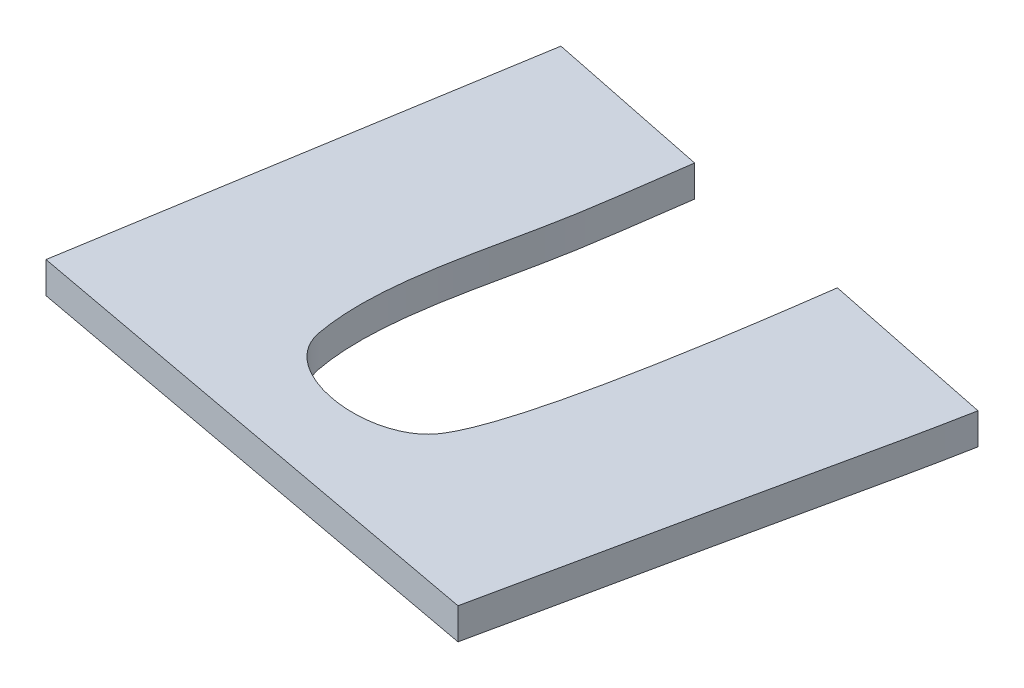
SolidWorks part; units mm, degrees
ref_plane "Front Plane" through (0, 0, 0) normal (0, 0, 1) x (1, 0, 0)
ref_plane "Top Plane" through (0, 0, 0) normal (0, 1, 0) x (1, 0, 0)
ref_plane "Right Plane" through (0, 0, 0) normal (1, 0, 0) x (0, 0, -1)
sketch "Sketch1" plane through (0, 0, 0) normal (0, 1, 0) x (1, 0, 0)
  line L0 (65.6854, -45.7865) -> (145.9282, -45.7865) construction
  line L2 (105.4165, 31.1383) -> (105.1558, -6.4062)
  line L3 (105.1558, -6.4062) -> (104.7647, -24.3962)
  line L4 (104.7647, -24.3962) -> (88.339, -24.1355)
  line L5 (88.339, -24.1355) -> (87.5568, 23.7076)
  line L6 (87.5568, 23.7076) -> (86.6443, 23.4469)
  line L7 (86.6443, 23.4469) -> (81.169, -31.0447)
  line L8 (81.169, -31.0447) -> (64.8737, -29.4804)
  line L9 (64.8737, -29.4804) -> (68.9149, 25.272)
  line L10 (68.9149, 25.272) -> (67.872, 25.1416)
  line L11 (67.872, 25.1416) -> (61.3539, -10.3171)
  line L12 (56.5305, -35.6074) -> (40.3655, -32.6091)
  line L13 (40.3655, -32.6091) -> (50.4034, 28.531)
  line L14 (50.4034, 28.531) -> (49.3605, 28.4007)
  line L15 (49.3605, 28.4007) -> (39.844, -6.1454)
  line L16 (32.8045, -31.0447) -> (17.0306, -26.7428)
  line L17 (17.0306, -26.7428) -> (21.0718, -9.7956)
  line L18 (21.0718, -9.7956) -> (27.7203, 14.5822)
  line L19 (27.7203, 14.5822) -> (34.3688, 40.6548)
  line L20 (39.844, 36.3528) -> (44.5371, 35.1795)
  line L21 (44.5371, 35.1795) -> (43.2335, 30.4865)
  line L22 (43.2335, 30.4865) -> (38.6708, 31.7901)
  line L23 (38.6708, 31.7901) -> (39.844, 36.3528)
  line L24 (57.7037, 32.3116) -> (62.5272, 31.399)
  line L25 (62.5272, 31.399) -> (61.6146, 26.706)
  line L26 (61.6146, 26.706) -> (56.9216, 27.4881)
  line L27 (56.9216, 27.4881) -> (57.7037, 32.3116)
  line L28 (75.8242, 29.7043) -> (80.6476, 29.1828)
  line L29 (80.6476, 29.1828) -> (80.2565, 24.4898)
  line L30 (80.2565, 24.4898) -> (75.4331, 24.8809)
  line L31 (75.4331, 24.8809) -> (75.8242, 29.7043)
  line L32 (37.3672, 28.9221) -> (42.9727, 27.3578)
  line L33 (31.7616, 7.4123) -> (37.3672, 28.9221)
  line L34 (94.2053, 28.6614) -> (99.0287, 28.531)
  line L35 (99.0287, 28.531) -> (98.8984, 23.838)
  line L36 (98.8984, 23.838) -> (94.2053, 23.9683)
  line L37 (94.2053, 23.9683) -> (94.2053, 28.6614)
  line L38 (55.8787, 24.4898) -> (61.4843, 23.5773)
  line L39 (61.4843, 23.5773) -> (61.6146, 23.0558)
  line L40 (74.6509, 21.7522) -> (80.5172, 21.2307)
  line L41 (93.6838, 20.7093) -> (99.5502, 20.5789)
  line L42 (99.4198, -9.0134) -> (93.6838, -8.8831)
  line L43 (31.6312, -14.8797) -> (26.156, -13.3154)
  line L44 (77.2581, -15.2708) -> (71.5222, -14.7494)
  line L45 (54.0536, -19.5728) -> (48.3176, -18.5299)
  line L46 (93.6838, -10.1867) -> (99.5502, -10.3171)
  line L47 (25.7649, -14.4887) -> (31.3705, -15.9226)
  line L48 (23.4183, -24.0051) -> (25.7649, -14.4887)
  line L49 (71.3918, -15.9226) -> (77.1278, -16.4441)
  line L50 (48.0569, -19.5728) -> (53.7929, -20.7461)
  spline S0 degree 3 poles (34.3688, 40.6548) (40.7566, 39.047) (47.0864, 37.1883) (53.5321, 35.8313) (59.4811, 34.5789) (65.4868, 33.5633) (71.5222, 32.833) (82.7525, 31.4742) (94.1059, 31.3316) (105.4165, 31.1383) knots 0 0 0 0 1 1 1 2 2 2 3 3 3 3
  spline S1 degree 3 poles (61.3539, -10.3171) (60.5564, -15.1018) (59.9234, -19.9204) (58.877, -24.657) (58.0717, -28.3021) (57.3126, -31.9573) (56.5305, -35.6074) knots 0 0 0 0 1 1 1 2 2 2 2
  spline S2 degree 3 poles (39.844, -6.1454) (38.6037, -10.974) (37.5703, -15.8635) (36.0635, -20.6157) (34.9627, -24.0875) (33.8908, -27.5684) (32.8045, -31.0447) knots 0 0 0 0 1 1 1 2 2 2 2
  spline S3 degree 3 poles (42.9727, 27.3578) (42.6098, 25.543) (42.0183, 23.7712) (41.5388, 22.0129) (40.5659, 18.4459) (39.615, 14.8641) (38.6708, 11.3232) (38.3128, 9.9807) (37.6374, 5.782) (36.3242, 5.0657) (36.0465, 4.9143) (35.7159, 4.8919) (35.4117, 4.805) knots 0 0 0 0 1 1 1 2 2 2 3 3 3 4 4 4 4
  spline S4 degree 3 poles (35.4117, 4.805) (35.3683, 4.8485) (35.3416, 4.9233) (35.2813, 4.9354) (34.8955, 5.0126) (34.4939, 4.9886) (34.1081, 5.0657) (32.6203, 5.3633) (32.0189, 5.8682) (31.7616, 7.4123) knots 0 0 0 0 1 1 1 2 2 2 3 3 3 3
  spline S5 degree 3 poles (61.6146, 23.0558) (61.5712, 23.0123) (61.4951, 22.9859) (61.4843, 22.9254) (61.1889, 21.28) (60.9974, 19.6171) (60.7021, 17.9717) (60.4799, 16.7336) (60.0077, 14.6452) (59.7895, 13.409) (59.5288, 11.9315) (59.2681, 10.4541) (59.0074, 8.9766) (58.5651, 6.4706) (58.3671, 3.9272) (57.5734, 1.546) (57.2884, 0.6909) (56.5034, 0.8671) (56.009, 0.3727) knots 0 0 0 0 1 1 1 2 2 2 3 3 3 4 4 4 5 5 5 6 6 6 6
  spline S6 degree 3 poles (56.009, 0.3727) (55.9656, 0.4161) (55.9396, 0.4949) (55.8787, 0.5031) (55.5536, 0.5464) (53.0297, 0.6407) (52.6196, 1.2852) (51.9043, 2.4092) (52.2987, 3.9943) (52.4892, 5.0657) (53.3606, 9.9671) (54.1038, 14.7799) (54.9661, 19.6664) (55.2268, 21.1438) (55.4876, 22.6213) (55.7483, 24.0987) (55.759, 24.1592) (55.8592, 24.1708) (55.8787, 24.2291) (55.9061, 24.3115) (55.8787, 24.4029) (55.8787, 24.4898) knots 0 0 0 0 1 1 1 2 2 2 3 3 3 4 4 4 5 5 5 6 6 6 7 7 7 7
  spline S7 degree 3 poles (80.5172, 21.2307) (80.0392, 15.6686) (79.6003, 10.1029) (79.0832, 4.5443) (79.0775, 4.4831) (78.963, 4.4746) (78.9529, 4.4139) (78.826, 3.6525) (78.8807, 1.9872) (77.91, 1.546) (77.5837, 1.3977) (77.2251, 1.3001) (76.8671, 1.2852) (74.9681, 1.2061) (73.2767, 1.3602) (73.2169, 3.6318) (73.1849, 4.8488) (73.2635, 6.0673) (73.3473, 7.2819) (73.3515, 7.3432) (73.4721, 7.3511) (73.4776, 7.4123) (73.9079, 12.1889) (74.2598, 16.9722) (74.6509, 21.7522) knots 0 0 0 0 1 1 1 2 2 2 3 3 3 4 4 4 5 5 5 6 6 6 7 7 7 8 8 8 8
  spline S8 degree 3 poles (99.5502, 20.5789) (99.5292, 18.1925) (100.7408, 9.6804) (99.1591, 4.9354) (99.0178, 4.5115) (98.3729, 4.0848) (97.9858, 4.0228) (97.3343, 3.9186) (94.7895, 3.5063) (94.2053, 4.6747) (94.0209, 5.0434) (93.8276, 5.4359) (93.8142, 5.8479) (93.6532, 10.7993) (93.7273, 15.7555) (93.6838, 20.7093) knots 0 0 0 0 1 1 1 2 2 2 3 3 3 4 4 4 5 5 5 5
  spline S9 degree 3 poles (93.6838, -8.8831) (93.7381, -4.9776) (93.2303, -1.8325) (94.0749, 1.546) (94.2734, 2.34) (95.3786, 2.8868) (96.1607, 2.8496) (96.8606, 2.8163) (97.5625, 2.7409) (98.2465, 2.5889) (98.4265, 2.5489) (98.5481, 2.3589) (98.6376, 2.1978) (98.8264, 1.858) (99.0648, 1.5319) (99.1591, 1.1549) (99.329, 0.4751) (99.4018, -0.2305) (99.4198, -0.9309) (99.4889, -3.6242) (99.4198, -6.3193) (99.4198, -9.0134) knots 0 0 0 0 1 1 1 2 2 2 3 3 3 4 4 4 5 5 5 6 6 6 7 7 7 7
  spline S10 degree 3 poles (26.156, -13.3154) (26.5473, -11.1629) (27.1698, -8.9703) (27.8507, -6.9276) (28.181, -5.9365) (28.5376, -4.1432) (29.2847, -3.1471) (30.1612, -1.9784) (33.0544, -2.5643) (33.717, -3.6686) (33.8584, -3.9042) (33.9663, -4.1761) (33.9777, -4.4507) (34.0665, -6.5814) (33.3414, -8.5642) (32.8045, -10.5778) (32.4111, -12.053) (32.0449, -13.4318) (31.6312, -14.8797) knots 0 0 0 0 1 1 1 2 2 2 3 3 3 4 4 4 5 5 5 6 6 6 6
  spline S11 degree 3 poles (71.5222, -14.7494) (71.7395, -12.0987) (71.9178, -9.4445) (72.174, -6.7973) (72.1799, -6.7361) (72.2915, -6.727) (72.3044, -6.6669) (72.4857, -5.8207) (72.4934, -4.085) (73.4776, -3.5382) (74.7635, -2.8238) (77.5508, -3.0117) (77.7796, -4.8418) (78.1927, -8.1469) (77.532, -12.0533) (77.2581, -15.2708) knots 0 0 0 0 1 1 1 2 2 2 3 3 3 4 4 4 5 5 5 5
  spline S12 degree 3 poles (48.3176, -18.5299) (48.4682, -17.6074) (49.3932, -9.6418) (50.7945, -7.8402) (51.7213, -6.6485) (54.6235, -7.2853) (55.2268, -8.492) (55.8006, -9.6395) (55.3934, -11.4371) (55.2268, -12.4029) (55.0096, -13.663) (54.8079, -14.926) (54.575, -16.1834) (54.3669, -17.3074) (54.2274, -18.443) (54.0536, -19.5728) knots 0 0 0 0 1 1 1 2 2 2 3 3 3 4 4 4 5 5 5 5
  spline S13 degree 3 poles (99.5502, -10.3171) (99.5067, -13.3154) (99.5054, -16.3146) (99.4198, -19.3121) (99.418, -19.3735) (99.3015, -19.3822) (99.2894, -19.4424) (99.1051, -20.3644) (99.0318, -21.7625) (97.7251, -21.9193) (97.6585, -21.9273) (95.19, -22.2702) (94.5964, -21.5282) (94.042, -20.8353) (93.862, -19.7496) (93.8142, -18.921) (93.7141, -17.1852) (93.7098, -15.445) (93.6838, -13.7065) (93.6663, -12.5333) (93.6838, -11.36) (93.6838, -10.1867) knots 0 0 0 0 1 1 1 2 2 2 3 3 3 4 4 4 5 5 5 6 6 6 7 7 7 7
  spline S14 degree 3 poles (31.3705, -15.9226) (30.9772, -17.7579) (30.4209, -19.4915) (29.9365, -21.2675) (29.4951, -22.8858) (29.203, -24.6491) (28.2418, -26.0909) (28.0279, -26.4117) (27.2093, -26.8922) (26.8078, -26.8731) (26.4958, -26.8583) (24.4443, -26.5211) (23.9398, -25.9606) (23.5046, -25.477) (23.4904, -24.5814) (23.4183, -24.0051) knots 0 0 0 0 1 1 1 2 2 2 3 3 3 4 4 4 5 5 5 5
  spline S15 degree 3 poles (77.1278, -16.4441) (77.1137, -16.6412) (76.8294, -26.002) (75.5634, -27.3946) (75.0354, -27.9754) (74.4265, -27.9481) (73.7383, -28.0464) knots 0 0 0 0 1 1 1 2 2 2 2
  spline S16 degree 3 poles (73.7383, -28.0464) (73.1325, -27.4405) (72.0165, -28.1085) (71.3918, -27.3946) (70.9276, -26.864) (70.7525, -25.5861) (70.74, -25.048) (70.7087, -23.7006) (70.7863, -22.352) (70.8704, -21.0068) (70.8742, -20.9455) (70.9945, -20.9376) (71.0007, -20.8764) (71.1697, -19.2287) (71.2615, -17.5739) (71.3918, -15.9226) knots 0 0 0 0 1 1 1 2 2 2 3 3 3 4 4 4 5 5 5 5
  spline S17 degree 3 poles (53.7929, -20.7461) (53.7097, -21.2553) (52.6819, -29.4762) (51.4463, -31.1751) (50.4846, -32.4974) (47.0812, -32.066) (46.7533, -30.2625) (46.3263, -27.9143) (47.1317, -25.3533) (47.5354, -23.0926) (47.7439, -21.925) (47.8831, -20.7461) (48.0569, -19.5728) knots 0 0 0 0 1 1 1 2 2 2 3 3 3 4 4 4 4
  dimension "D1" = 16.35
extrude "Boss-Extrude1" add sketch "Sketch1" along normal blind 1
sketch "Sketch2" plane through (0, 1, 0) normal (0, 1, 0) x (1, 0, 0)
  line L0 (34.3688, 40.6548) -> (34.1217, 39.6858)
  line L1 (34.3688, 40.6548) -> (27.7203, 14.5822) construction
  line L6 (105.1558, -6.4062) -> (105.4165, 31.1383) construction
  line L7 (105.4095, 30.1383) -> (105.4165, 31.1383)
  arc A0 (34.3688, 40.6548) -> (105.4165, 31.1383) centre (102.0623, 276.0676) ccw
  arc A1 (34.1217, 39.6858) -> (105.4095, 30.1383) centre (102.1959, 277.0586) ccw
  dimension "D1" = 1
  dimension "D2" = 1
  dimension "D3" = 1
extrude "Boss-Extrude2" add sketch "Sketch2" along normal blind 2.42 and the other way blind 1
fillet "Fillet1" radius 0.5 2 edges at (69.5427, 3.42, -33.2836) (69.4162, 3.42, -32.3027)
sketch "Sketch3" plane through (0, 1, 0) normal (0, 1, 0) x (1, 0, 0)
  line L20 (37.3672, 28.9221) -> (42.9727, 27.3578)
  line L39 (42.9727, 27.3578) -> (48.6429, 25.7958)
  line L40 (39.844, -6.1454) -> (49.3605, 28.4007) construction
  line L41 (37.3672, 28.9221) -> (31.7427, 30.3564)
  line L42 (34.1217, 39.6858) -> (27.7203, 14.5822) construction
  line L43 (31.7427, 30.3564) -> (31.9898, 31.3253)
  line L45 (48.9085, 26.7599) -> (48.6429, 25.7958)
  line L46 (31.9898, 31.3253) -> (48.9085, 26.7599)
  line L47 (55.8787, 24.4898) -> (61.4843, 23.5773)
  line L48 (61.4843, 23.5773) -> (67.4072, 22.613)
  line L49 (61.3539, -10.3171) -> (67.872, 25.1416) construction
  line L50 (55.8787, 24.4898) -> (49.9011, 25.4712)
  line L51 (50.4034, 28.531) -> (40.3655, -32.6091) construction
  line L52 (49.9011, 25.4712) -> (50.0631, 26.458)
  line L53 (67.4072, 22.613) -> (67.588, 23.5966)
  line L54 (50.0631, 26.458) -> (67.588, 23.5966)
  line L55 (74.6509, 21.7522) -> (80.5172, 21.2307)
  line L56 (80.5172, 21.2307) -> (74.6509, 21.7522) construction
  line L57 (80.5172, 21.2307) -> (86.3626, 20.6434)
  line L58 (81.169, -31.0447) -> (86.6443, 23.4469) construction
  line L59 (74.6509, 21.7522) -> (68.6876, 22.1923)
  line L60 (68.9149, 25.272) -> (64.8737, -29.4804) construction
  line L61 (68.6876, 22.1923) -> (68.7612, 23.1896)
  line L62 (86.3626, 20.6434) -> (86.4625, 21.6384)
  line L63 (68.7612, 23.1896) -> (86.4625, 21.6384)
  line L64 (93.6838, 20.7093) -> (99.5502, 20.5789)
  line L65 (99.5502, 20.5789) -> (105.3432, 20.5789)
  line L66 (105.1558, -6.4062) -> (105.4095, 30.1383) construction
  line L67 (93.6838, 20.7093) -> (87.6036, 20.8444)
  line L68 (87.5568, 23.7076) -> (88.339, -24.1355) construction
  line L69 (87.6036, 20.8444) -> (87.5873, 21.8443)
  line L70 (105.3432, 20.5789) -> (105.3501, 21.5789)
  line L71 (87.5873, 21.8443) -> (105.3501, 21.5789)
  spline S0 degree 3 poles (74.6509, 21.7522) (74.2598, 16.9722) (73.9079, 12.1889) (73.4776, 7.4123) (73.4721, 7.3511) (73.3515, 7.3432) (73.3473, 7.2819) (73.2635, 6.0673) (73.1849, 4.8488) (73.2169, 3.6318) (73.2767, 1.3602) (74.9681, 1.2061) (76.8671, 1.2852) (77.2251, 1.3001) (77.5837, 1.3977) (77.91, 1.546) (78.8807, 1.9872) (78.826, 3.6525) (78.9529, 4.4139) (78.963, 4.4746) (79.0775, 4.4831) (79.0832, 4.5443) (79.6003, 10.1029) (80.0392, 15.6686) (80.5172, 21.2307) knots 0 0 0 0 1 1 1 2 2 2 3 3 3 4 4 4 5 5 5 6 6 6 7 7 7 8 8 8 8 construction
  dimension "D1" = 1
  dimension "D2" = 1
  dimension "D3" = 1
  dimension "D4" = 1
  dimension "D5" = 1
  dimension "D6" = 1
  dimension "D7" = 1
  dimension "D8" = 1
extrude "Boss-Extrude3" add sketch "Sketch3" along normal blind 2.42
fillet "Fillet2" radius 0.45 14 edges at (52.8899, 3.42, -24.9805) (61.6429, 3.42, -23.5514) (71.6693, 3.42, -21.9722) (83.4399, 3.42, -20.9371) (77.584, 3.42, -21.4914) (102.4467, 3.42, -20.5789) (93.5769, 3.42, -20.7117) (96.4687, 3.42, -21.7116) (77.6119, 3.42, -22.414) (58.8255, 3.42, -25.0273) (40.4492, 3.42, -29.0426) (34.5549, 3.42, -29.6392) (45.8078, 3.42, -26.5768) (40.1699, 3.42, -28.1399)
sketch "Sketch4" plane through (0, 1, 0) normal (0, 1, 0) x (1, 0, 0)
  line L0 (30.8433, 26.8292) -> (34.884, 25.7988)
  line L3 (47.4107, 21.3224) -> (43.3904, 22.4299)
  line L4 (39.844, -6.1454) -> (48.6429, 25.7958) construction
  line L5 (31.7427, 30.3564) -> (27.7203, 14.5822) construction
  line L6 (34.884, 25.7988) -> (34.6369, 24.8299)
  line L7 (34.6369, 24.8299) -> (30.5962, 25.8602)
  line L8 (30.5962, 25.8602) -> (30.8433, 26.8292)
  line L9 (43.3904, 22.4299) -> (43.656, 23.394)
  line L10 (43.656, 23.394) -> (47.6762, 22.2865)
  line L11 (47.6762, 22.2865) -> (47.4107, 21.3224)
  line L12 (31.7427, 30.3564) -> (37.3672, 28.9221) construction
  line L13 (48.6429, 25.7958) -> (42.9727, 27.3578) construction
  line L14 (49.3113, 21.8793) -> (53.3473, 21.2167)
  line L15 (49.9011, 25.4712) -> (40.3655, -32.6091) construction
  line L16 (53.3473, 21.2167) -> (53.1853, 20.2299)
  line L17 (53.1853, 20.2299) -> (49.1493, 20.8925)
  line L18 (49.3113, 21.8793) -> (49.1493, 20.8925)
  line L19 (49.9011, 25.4712) -> (55.8787, 24.4898) construction
  line L27 (66.7491, 19.033) -> (62.7265, 19.7725)
  line L28 (61.3539, -10.3171) -> (67.4072, 22.613) construction
  line L29 (62.7265, 19.7725) -> (62.5457, 18.789)
  line L30 (62.5457, 18.789) -> (66.5683, 18.0495)
  line L32 (66.5683, 18.0495) -> (66.7491, 19.033)
  line L33 (68.3461, 17.5649) -> (72.425, 17.2638)
  line L34 (68.6876, 22.1923) -> (64.8737, -29.4804) construction
  line L35 (72.425, 17.2638) -> (72.4986, 18.2611)
  line L36 (72.4986, 18.2611) -> (68.4197, 18.5622)
  line L37 (68.4197, 18.5622) -> (68.3461, 17.5649)
  line L38 (68.6876, 22.1923) -> (74.6509, 21.7522) construction
  line L39 (85.8987, 16.0266) -> (81.8292, 16.4355)
  line L40 (81.169, -31.0447) -> (86.3626, 20.6434) construction
  line L41 (81.8292, 16.4355) -> (81.9291, 17.4305)
  line L42 (81.9291, 17.4305) -> (85.9987, 17.0216)
  line L43 (85.9987, 17.0216) -> (85.8987, 16.0266)
  line L44 (80.5172, 21.2307) -> (86.3626, 20.6434) construction
  line L45 (87.681, 16.111) -> (91.771, 16.1779)
  line L46 (87.6036, 20.8444) -> (88.339, -24.1355) construction
  line L47 (91.771, 16.1779) -> (91.771, 17.1109)
  line L48 (91.771, 17.1109) -> (87.6646, 17.1109)
  line L49 (87.6646, 17.1109) -> (87.681, 16.111)
  line L52 (87.6036, 20.8444) -> (93.6838, 20.7093) construction
  line L53 (105.3179, 16.9389) -> (101.2211, 16.9674)
  line L54 (105.1558, -6.4062) -> (105.3432, 20.5789) construction
  line L55 (101.2211, 16.9674) -> (101.2211, 15.9674)
  line L56 (101.2211, 15.9674) -> (105.3111, 15.9674)
  line L57 (105.3111, 15.9674) -> (105.3179, 16.9389)
  point P16 (43.5232, 22.9119)
  dimension "D1" = 3.64
  dimension "D2" = 1
  dimension "D3" = 4.17
  dimension "D4" = 3.64
  dimension "D5" = 1
  dimension "D6" = 4.17
  dimension "D7" = 3.64
  dimension "D8" = 1
  dimension "D9" = 4.09
  dimension "D10" = 3.64
  dimension "D11" = 1
  dimension "D12" = 4.09
  dimension "D13" = 3.64
  dimension "D14" = 1
  dimension "D15" = 4.09
  dimension "D16" = 3.64
  dimension "D17" = 1
  dimension "D18" = 4.09
  dimension "D19" = 1
  dimension "D20" = 4.09
  dimension "D21" = 3.64
  dimension "D22" = 1
  dimension "D23" = 4.09
  dimension "D24" = 3.64
extrude "Boss-Extrude4" add sketch "Sketch4" along normal blind 2.42
fillet "Fillet3" radius 0.45 16 edges at (103.2661, 3.42, -15.9674) (103.2695, 3.42, -16.9531) (89.726, 3.42, -16.1444) (89.7178, 3.42, -17.1109) (83.9639, 3.42, -17.2261) (83.8639, 3.42, -16.2311) (70.3855, 3.42, -17.4144) (70.4591, 3.42, -18.4117) (64.7378, 3.42, -19.4028) (64.557, 3.42, -18.4192) (51.1673, 3.42, -20.5612) (51.3293, 3.42, -21.548) (45.6661, 3.42, -22.8402) (45.4005, 3.42, -21.8762) (32.8636, 3.42, -26.314) (32.6165, 3.42, -25.345)
sketch "Sketch5" plane through (0, 0, 0) normal (0, -1, 0) x (1, 0, 0)
  line L0 (59.6663, 20.6899) -> (54.0536, 19.5728)
  line L1 (54.0536, 19.5728) -> (48.3176, 18.5299)
  line L2 (48.3176, 18.5299) -> (42.8405, 17.5341)
  line L3 (50.4034, -28.531) -> (40.3655, 32.6091) construction
  line L4 (42.8405, 17.5341) -> (34.7668, 31.6899)
  line L5 (34.7668, 31.6899) -> (14.2764, 27.9644)
  line L6 (14.2764, 27.9644) -> (30.9939, -44.5578)
  line L7 (30.9939, -44.5578) -> (106.4895, -32.163)
  line L8 (106.4895, -32.163) -> (109.5231, 31.6899)
  line L9 (109.5231, 31.6899) -> (62.5503, 33.9215)
  line L10 (62.5503, 33.9215) -> (59.6663, 20.6899)
  spline S0 degree 3 poles (56.5305, 35.6074) (57.3126, 31.9573) (58.0717, 28.3021) (58.877, 24.657) (59.9234, 19.9204) (60.5564, 15.1018) (61.3539, 10.3171) knots 0 0 0 0 1 1 1 2 2 2 2 construction
extrude "Cut-Extrude1" cut sketch "Sketch5" against normal blind 10
sketch "Sketch6" plane through (0, 1, 0) normal (0, 1, 0) x (1, 0, 0)
  line L3 (42.8405, -17.5341) -> (40.3655, -32.6091) construction
  line L4 (42.6861, -18.4742) -> (59.4417, -21.9015)
  line L5 (59.4417, -21.9015) -> (60.6999, -20.4662)
  line L6 (60.6999, -20.4662) -> (41.603, -16.1807)
  line L7 (41.603, -16.1807) -> (42.6861, -18.4742)
  spline S0 degree 3 poles (56.5305, -35.6074) (57.3126, -31.9573) (58.0717, -28.3021) (58.877, -24.657) (59.1679, -23.3401) (59.4269, -22.0169) (59.6663, -20.6899) knots 0 0 0 0 1 1 1 1.278017 1.278017 1.278017 1.278017 construction
extrude "Cut-Extrude2" cut sketch "Sketch6" against normal blind 10
